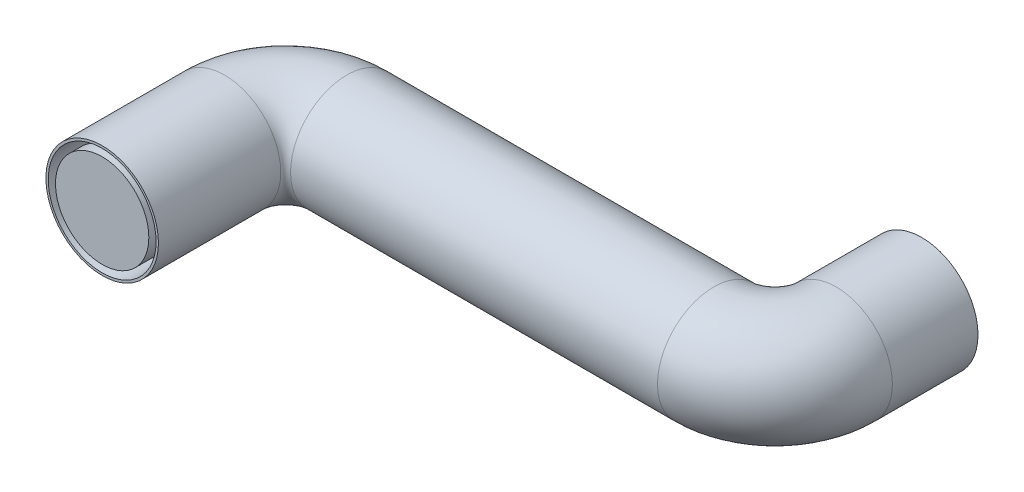
SolidWorks part; units mm, degrees
ref_plane "Front Plane" through (0, 0, 0) normal (0, 0, 1) x (1, 0, 0)
ref_plane "Top Plane" through (0, 0, 0) normal (0, 1, 0) x (1, 0, 0)
ref_plane "Right Plane" through (0, 0, 0) normal (1, 0, 0) x (0, 0, -1)
sketch "Sketch2" plane through (0, 0, 0) normal (0, 1, 0) x (1, 0, 0)
  line L0 (0, 120) -> (0, 50)
  line L1 (-50, 0) -> (-350, 0)
  line L3 (-400, -50) -> (-400, -150)
  arc A0 (-350, 0) -> (-400, -50) centre (-350, -50) ccw
  arc A1 (0, 50) -> (-50, 0) centre (-50, 50) cw
  point P7 (-400, 0)
  point P10 (0, 0)
  dimension "D4" = 50
  dimension "D5" = 50
  dimension "D1" = 400
  dimension "D2" = 120
  dimension "D3" = 150
sketch "Sketch4" plane through (0, 0, 0) normal (0, 0, 1) x (1, 0, 0)
  line L0 (-50, 0) -> (-350, 0) construction
  circle A0 centre (-400, 0) radius 38.1557
extrude "Boss-Extrude1" add sketch "Sketch4" along normal blind 150
sketch "Sketch5" plane through (0, 0, 150) normal (0, 0, 1) x (1, 0, 0)
  line L0 (-50, 0) -> (-350, 0) construction
  circle A0 centre (-400, 0) radius 44.09
  circle A1 centre (-400, 0) radius 46
  dimension "D1" = 88.18
  dimension "D2" = 92
sweep "Sweep2" add profiles "Sketch5" path "Sketch2"
sketch "Sketch6" plane through (0, 0, 0) normal (0, 0, -1) x (-1, 0, 0)
  arc A1 (408.7407, 37.1411) -> (408.7407, -37.1411) centre (391.0991, 0) cw
  arc A3 (408.7407, -37.1411) -> (408.7407, 37.1411) centre (400, 0) ccw
  spline S1 degree 3 poles (1128.8713, 1881.3793) (-157.5138, -329.1588) (312.2066, 126.9202) (418.42, 30.1524) (418.7733, 29.8202) (419.4662, 29.1479) (419.8063, 28.8073) (420.808, 27.7717) (421.4506, 27.0633) (423.3031, 24.8837) (424.4376, 23.3585) (426.4985, 20.1585) (427.4249, 18.4837) (428.4418, 16.2887) (428.6381, 15.8445) (429.0127, 14.954) (429.1916, 14.5067) (429.703, 13.1585) (430.0104, 12.2515) (430.8328, 9.5063) (431.2485, 7.6437) (431.6686, 4.8001) (431.7746, 3.844) (431.881, 2.3969) (431.9076, 1.9119) (431.9429, 0.9425) (431.9515, 0.4554) (431.9498, -1.9597) (431.8066, -3.8671) (431.2497, -7.6348) (430.8359, -9.495) (430.1485, -11.7907) (430.0025, -12.2483) (429.6932, -13.1606) (429.5297, -13.6158) (429.017, -14.9663) (428.6449, -15.8498) (427.4407, -18.4511) (426.5211, -20.1201) (424.9726, -22.5294) (424.4281, -23.3168) (423.2827, -24.8599) (422.6801, -25.6172) (420.8131, -27.8123) (419.4828, -29.1833) (416.6632, -31.7536) (415.1739, -32.9528) (412.8253, -34.6279) (412.0231, -35.1655) (303.232, -103.7386) (-14.5908, 256.3756) (926.5667, -1952.3993) knots -4.507468 -4.507468 -4.507468 -4.507468 0.125 0.125 0.140625 0.140625 0.15625 0.15625 0.1875 0.1875 0.25 0.25 0.3125 0.3125 0.328125 0.328125 0.34375 0.34375 0.375 0.375 0.4375 0.4375 0.46875 0.46875 0.484375 0.484375 0.5 0.5 0.5625 0.5625 0.625 0.625 0.640625 0.640625 0.65625 0.65625 0.6875 0.6875 0.75 0.75 0.78125 0.78125 0.8125 0.8125 0.875 0.875 0.9375 0.9375 0.96875 0.96875 5.124995 5.124995 5.124995 5.124995 only from (408.7407, 37.1411) to (408.7407, -37.1411)
  spline S2 degree 3 poles (408.7407, 37.1411) (412.0853, 35.2801) (415.2066, 33.08) (418.42, 30.1524) (418.7733, 29.8202) (419.4662, 29.1479) (419.8063, 28.8073) (420.808, 27.7717) (421.4506, 27.0633) (423.3031, 24.8837) (424.4376, 23.3585) (426.4985, 20.1585) (427.4249, 18.4837) (428.4418, 16.2887) (428.6381, 15.8445) (429.0127, 14.954) (429.1916, 14.5067) (429.703, 13.1585) (430.0104, 12.2515) (430.8328, 9.5063) (431.2485, 7.6437) (431.6686, 4.8001) (431.7746, 3.844) (431.881, 2.3969) (431.9076, 1.9119) (431.9429, 0.9425) (431.9515, 0.4554) (431.9498, -1.9597) (431.8066, -3.8671) (431.2497, -7.6348) (430.8359, -9.495) (430.1485, -11.7907) (430.0025, -12.2483) (429.6932, -13.1606) (429.5297, -13.6158) (429.017, -14.9663) (428.6449, -15.8498) (427.4407, -18.4511) (426.5211, -20.1201) (424.9726, -22.5294) (424.4281, -23.3168) (423.2827, -24.8599) (422.6801, -25.6172) (420.8131, -27.8123) (419.4828, -29.1833) (416.6632, -31.7536) (415.1739, -32.9528) (412.8253, -34.6279) (412.0231, -35.1655) (410.3994, -36.1889) (409.5757, -36.6765) (408.7407, -37.1411) knots 0 0 0 0 0.125 0.125 0.140625 0.140625 0.15625 0.15625 0.1875 0.1875 0.25 0.25 0.3125 0.3125 0.328125 0.328125 0.34375 0.34375 0.375 0.375 0.4375 0.4375 0.46875 0.46875 0.484375 0.484375 0.5 0.5 0.5625 0.5625 0.625 0.625 0.640625 0.640625 0.65625 0.65625 0.6875 0.6875 0.75 0.75 0.78125 0.78125 0.8125 0.8125 0.875 0.875 0.9375 0.9375 0.96875 0.96875 1 1 1 1
  dimension "D1" = 0
extrude "Cut-Extrude1" cut sketch "Sketch6" against normal blind 140
